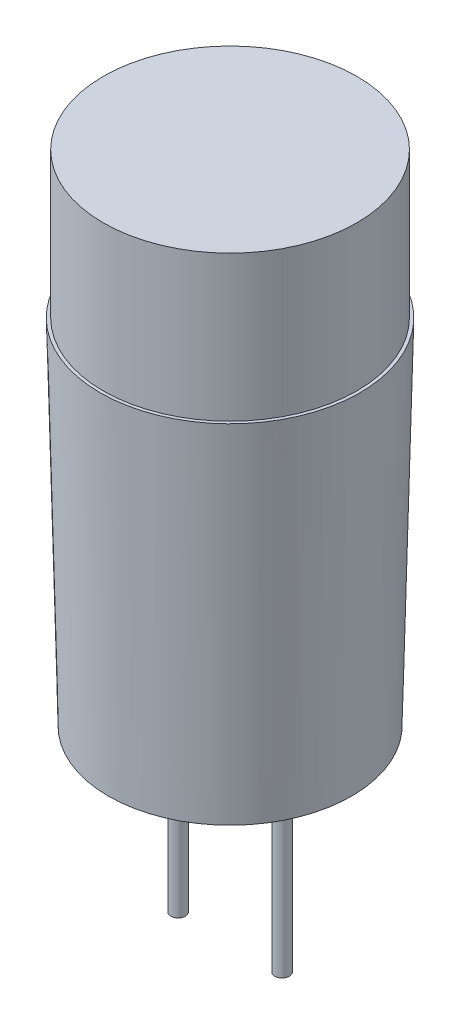
SolidWorks part; units mm, degrees
ref_plane "Front Plane" through (0, 0, 0) normal (0, 0, 1) x (1, 0, 0)
ref_plane "Top Plane" through (0, 0, 0) normal (0, 1, 0) x (1, 0, 0)
ref_plane "Right Plane" through (0, 0, 0) normal (1, 0, 0) x (0, 0, -1)
sketch "Sketch1" plane through (0, 0, 0) normal (0, 0, 1) x (1, 0, 0)
  line L0 (0, 0) -> (0, -8608.9452) construction
  line L1 (0, 0) -> (6.25, 0)
  line L2 (6.25, 0) -> (5.85, -17)
  line L3 (5.85, -17) -> (0, -17)
  line L4 (0, -17) -> (0, 0)
  dimension "D1" = 12.5
  dimension "D2" = 11.7
  dimension "D3" = 17
revolve "Revolve1" add sketch "Sketch1" angle 360 about L0
sketch "Sketch2" plane through (0, 0, 0) normal (0, 1, 0) x (1, 0, 0)
  circle A0 centre (0, 0) radius 6.1
  dimension "D1" = 12.2
extrude "Boss-Extrude1" add sketch "Sketch2" along normal blind 7
sketch "Sketch3" plane through (0, -17, 0) normal (0, -1, 0) x (1, 0, 0)
  line L0 (0, 0) -> (50000, 0) construction
  line L1 (0, 0) -> (0, -50000) construction
  circle A0 centre (-2.5, 0) radius 0.35
  circle A1 centre (2.5, 0) radius 0.35
  dimension "D1" = 0.7
  dimension "D2" = 5
extrude "Boss-Extrude2" add sketch "Sketch3" along normal blind 9
